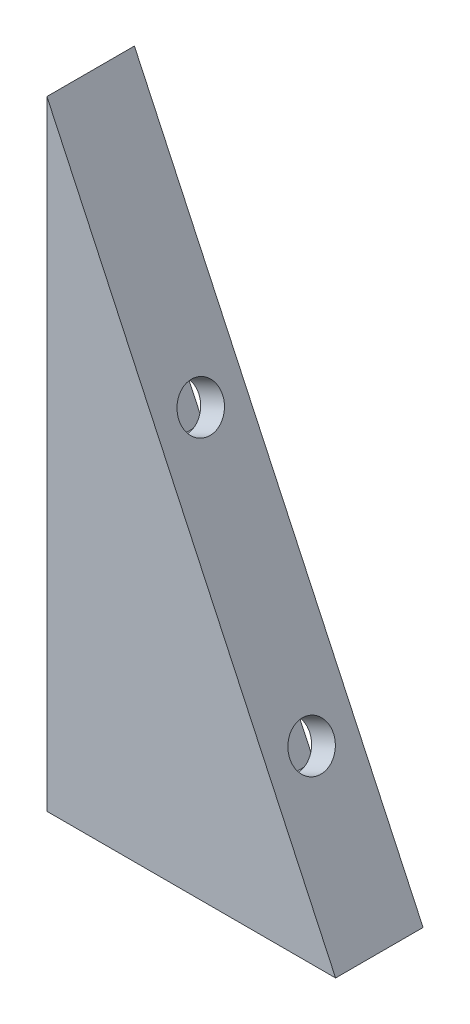
SolidWorks part; units mm, degrees
ref_plane "Front" through (0, 0, 0) normal (0, 0, 1) x (1, 0, 0)
ref_plane "Top" through (0, 0, 0) normal (0, 1, 0) x (1, 0, 0)
ref_plane "Right" through (0, 0, 0) normal (1, 0, 0) x (0, 0, -1)
sketch "Sketch1" plane through (0, 0, 0) normal (0, 0, 1) x (1, 0, 0)
  line L0 (0, 70.7687) -> (0, 0)
  line L1 (0, 0) -> (33, 0)
  line L2 (33, 0) -> (0, 70.7687)
  dimension "D1" = 33
  dimension "D2" = 65
extrude "Boss-Extrude1" add sketch "Sketch1" along normal blind 10
sketch "Sketch2" plane through (0, 0, 0) normal (0, -1, 0) x (-1, 0, 0)
  line L0 (-16.5, -10) -> (-16.5, 0) construction
  line L1 (-13.6, -6.9) -> (-19.4, -6.9)
  line L2 (-13.6, -6.9) -> (-13.6, -3.1)
  line L3 (-13.6, -3.1) -> (-19.4, -3.1)
  line L4 (-19.4, -6.9) -> (-19.4, -3.1)
  line L5 (-13.6, -6.9) -> (-19.4, -3.1) construction
  line L6 (-13.6, -3.1) -> (-19.4, -6.9) construction
  line L7 (0, -10) -> (-33, -10) construction
  line L8 (0, 0) -> (-33, 0) construction
  line L9 (0, -5) -> (-33, -5) construction
  line L10 (0, -10) -> (0, 0) construction
  line L11 (-33, -10) -> (-33, 0) construction
  point P0 (-16.5, -5)
  point P18 (-16.5, -5)
  dimension "D1" = 5.8
  dimension "D2" = 3.8
extrude "Boss-Extrude2" add sketch "Sketch2" along normal blind 2
sketch "Sketch3" plane through (0, 0, 0) normal (0, -1, 0) x (-1, 0, 0)
  circle A0 centre (-23.3315, -4) radius 2.15
  circle A1 centre (-8.5515, -4) radius 2.15
  dimension "D1" = 4.3
extrude "Cut-Extrude1" cut sketch "Sketch3" against normal blind 12
sketch "Sketch4" plane through (0, 0, 0) normal (0, 0, -1) x (-1, 0, 0)
  line L0 (-27.1315, 3.25) -> (-27.1315, 5) construction
  line L1 (-25.4815, -1.25) -> (-21.1815, -1.25) construction
  line L2 (-19.5315, 3.25) -> (-19.5315, 5) construction
  line L3 (-25.4815, 0) -> (-21.1815, 0)
  line L4 (-21.1815, 0) -> (-10.7015, 0) construction
  line L5 (-15.9415, 0) -> (-15.9415, 7.9966) construction
  line L7 (-12.3515, 3.25) -> (-12.3515, 5) construction
  line L8 (-25.4815, 0) -> (-25.4815, -2.5) construction
  line L10 (-19.5315, 5) -> (-19.5315, 3.25)
  line L12 (-27.1315, 3.25) -> (-27.1315, 5)
  line L13 (-23.3315, 5) -> (-23.3315, -5) construction
  line L14 (-35.3315, -5) -> (66.6685, -5) construction
  line L15 (-21.1815, -2.5) -> (-21.1815, 0) construction
  line L20 (-27.1315, 3.25) -> (-19.5315, 3.25)
  line L21 (-19.5315, 3.25) -> (-19.5315, 6.75)
  line L22 (-19.5315, 6.75) -> (-27.1315, 6.75)
  line L23 (-27.1315, 6.75) -> (-27.1315, 3.25)
  line L24 (-27.1315, 5) -> (-19.5315, 5) construction
  line L25 (-4.7515, 3.25) -> (-4.7515, 5) construction
  line L26 (-4.7515, 6.75) -> (-4.7515, 3.25)
  line L27 (-12.3515, 6.75) -> (-4.7515, 6.75)
  line L28 (-12.3515, 3.25) -> (-12.3515, 6.75)
  line L29 (-4.7515, 3.25) -> (-12.3515, 3.25)
  line L30 (-4.7515, 3.25) -> (-4.7515, 5)
  line L31 (-12.3515, 5) -> (-12.3515, 3.25)
  point P5 (-23.3315, 0)
  dimension "D1" = 7.6
  dimension "D2" = 3.8
  dimension "D3" = 3.5
extrude "Cut-Extrude2" cut sketch "Sketch4" against normal blind 6.5
sketch "Sketch5" plane through (0, 0, 0) normal (0, 0, -1) x (-1, 0, 0)
  line L0 (-21.1815, 0) -> (-10.7015, 0) construction
  line L1 (0, 0) -> (-33, 0) construction
  line L2 (-10.7015, 0) -> (-10.7015, -2.5) construction
  line L3 (-15.9415, 0) -> (-15.9415, 10.1006) construction
  line L4 (-27.1315, 6.75) -> (-27.1315, 3.25)
  line L5 (-27.1315, 3.25) -> (-19.5315, 3.25)
  line L6 (-19.5315, 3.25) -> (-19.5315, 6.75)
  line L7 (-19.5315, 6.75) -> (-27.1315, 6.75)
  line L8 (-12.3515, 6.75) -> (-4.7515, 6.75)
  line L9 (-12.3515, 3.25) -> (-12.3515, 6.75)
  line L10 (-4.7515, 3.25) -> (-12.3515, 3.25)
  line L11 (-4.7515, 6.75) -> (-4.7515, 3.25)
extrude "Cut-Extrude3" cut sketch "Sketch5" against normal blind 6.5
sketch "Sketch7" plane through (0, 0, 0) normal (0, 0, -1) x (-1, 0, 0)
  line L0 (0, 70.7687) -> (-12.5813, 43.7879)
  line L1 (-33, 0) -> (0, 70.7687) construction
  line L2 (0, 70.7687) -> (-25.2599, 16.5987)
  line L3 (-12.5813, 43.7879) -> (9.6124, 33.4388) construction
  line L5 (-25.2599, 16.5987) -> (-0.2852, 4.9528) construction
  line L6 (-8.2565, 45.9641) -> (-4.6312, 44.2736)
  line L7 (-4.6312, 44.2736) -> (-7.8431, 37.3856)
  line L8 (-7.8431, 37.3856) -> (-11.4684, 39.0761)
  line L11 (-20.935, 18.7748) -> (-17.3098, 17.0844)
  line L12 (-17.3098, 17.0844) -> (-20.5217, 10.1964)
  line L13 (-20.5217, 10.1964) -> (-24.1469, 11.8869)
  line L15 (-20.935, 18.7748) -> (-24.1469, 11.8869)
  line L16 (-8.2565, 45.9641) -> (-11.4684, 39.0761)
  dimension "D1" = 29.77
  dimension "D2" = 59.77
  dimension "D3" = 4
  dimension "D4" = 3
  dimension "D5" = 4
  dimension "D6" = 7.6
  dimension "D7" = 3.8
  dimension "D8" = 7.6
  dimension "D9" = 3.8
  dimension "D10" = 3
extrude "Cut-Extrude4" cut sketch "Sketch7" against normal blind 8.5 contours L6 L16 L8 L7 | L11 L15 L13 L12
sketch "Sketch8" plane through (27.106, 12.6397, 0) normal (0.9063, 0.4226, 0) x (0, 0, -1)
  line L0 (-5, 64.1382) -> (-5, 34.3682) construction
  line L1 (-10, 64.1382) -> (0, 64.1382) construction
  line L2 (-5, 64.1382) -> (-5, 4.3682) construction
  circle A1 centre (-5, 34.3682) radius 2.5
  circle A2 centre (-5, 4.3682) radius 2.5
  dimension "D3" = 5
  dimension "D4" = 5
  dimension "D1" = 29.77
  dimension "D2" = 59.77
extrude "Cut-Extrude5" cut sketch "Sketch8" against normal blind 10
